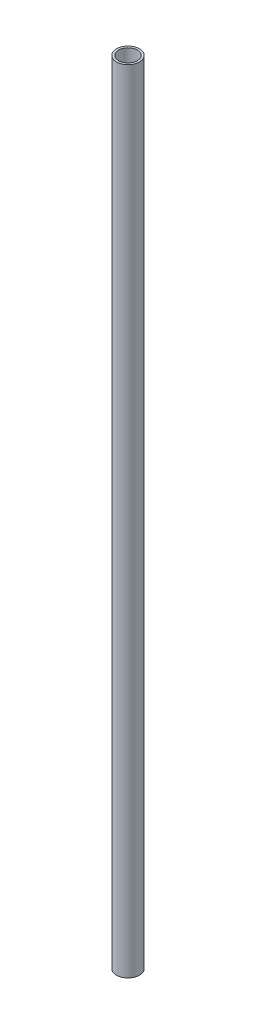
SolidWorks part; units mm, degrees
material "Thornel Mat VMA"
ref_plane "Front Plane" through (0, 0, 0) normal (0, 0, 1) x (1, 0, 0)
ref_plane "Top Plane" through (0, 0, 0) normal (0, 1, 0) x (1, 0, 0)
ref_plane "Right Plane" through (0, 0, 0) normal (1, 0, 0) x (0, 0, -1)
sketch "Sketch1" plane through (0, 0, 0) normal (0, 1, 0) x (1, 0, 0)
  circle A0 centre (0, 0) radius 4.825
  circle A1 centre (0, 0) radius 3.925
  dimension "D1" = 9.65
  dimension "D2" = 7.85
extrude "Boss-Extrude1" add sketch "Sketch1" along normal blind 333
